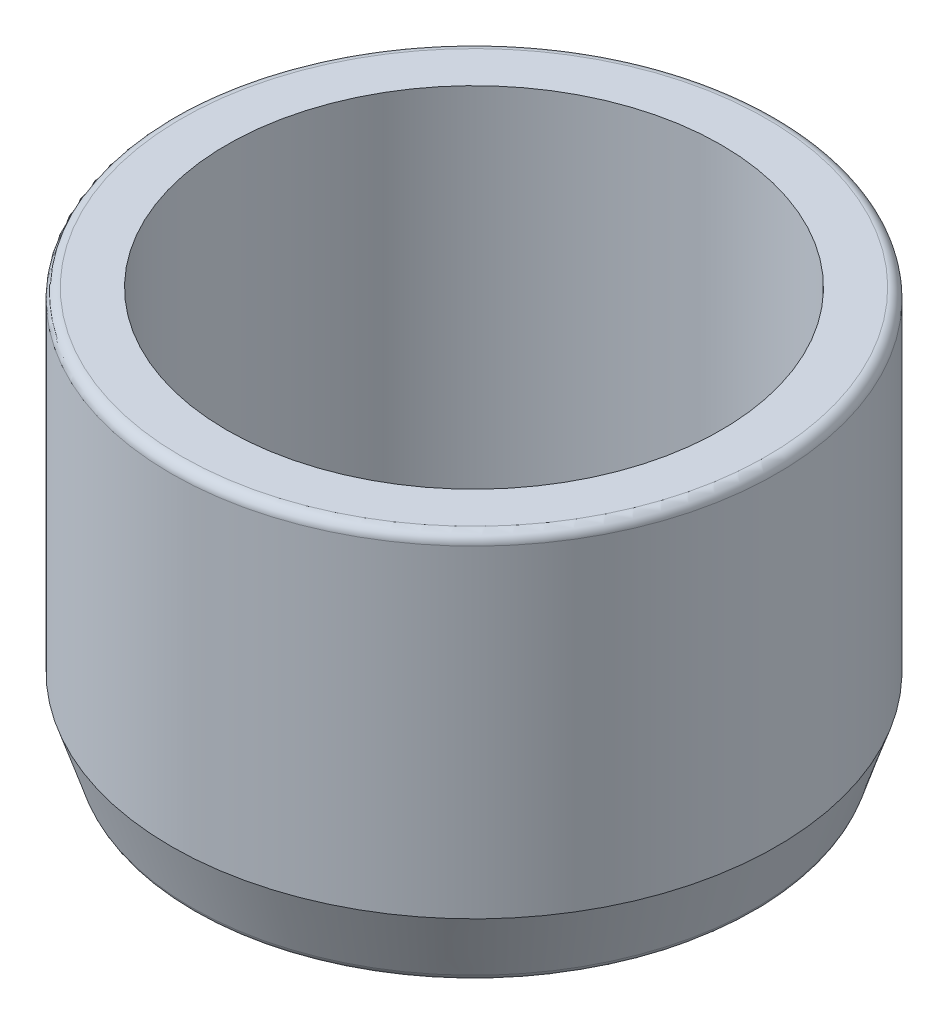
SolidWorks part; units mm, degrees
ref_plane "Front Plane" through (0, 0, 0) normal (0, 0, 1) x (1, 0, 0)
ref_plane "Top Plane" through (0, 0, 0) normal (0, 1, 0) x (1, 0, 0)
ref_plane "Right Plane" through (0, 0, 0) normal (1, 0, 0) x (0, 0, -1)
sketch "Sketch1" plane through (0, 0, 0) normal (0, 1, 0) x (1, 0, 0)
  circle A0 centre (0, 0) radius 30
  circle A1 centre (0, 0) radius 24.5
  dimension "D1" = 49
  dimension "D2" = 60
extrude "Boss-Extrude1" add sketch "Sketch1" along normal mid plane 40
chamfer "Chamfer2" distance 2.31 distance2 7 1 edges at (0, -20, 30)
fillet "Fillet1" radius 1 2 edges at (0, -20, 27.69) (0, 20, 30)
